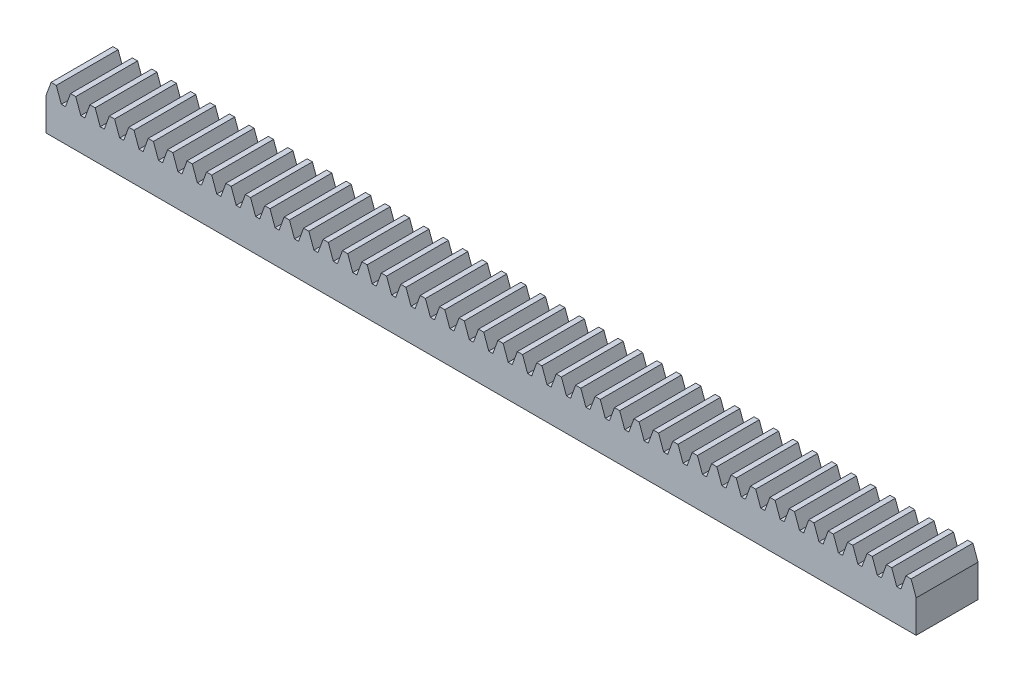
SolidWorks part; units mm, degrees
ref_plane "前视基准面" through (0, 0, 0) normal (0, 0, 1) x (1, 0, 0)
ref_plane "上视基准面" through (0, 0, 0) normal (0, 1, 0) x (1, 0, 0)
ref_plane "右视基准面" through (0, 0, 0) normal (1, 0, 0) x (0, 0, -1)
sketch "草图2" plane through (0, 0, 0) normal (0, 1, 0) x (1, 0, 0)
  line L1 (140.7108, -10) -> (-140.7108, -10)
  line L2 (140.7108, -10) -> (140.7108, 10)
  line L3 (140.7108, 10) -> (-140.7108, 10)
  line L4 (-140.7108, -10) -> (-140.7108, 10)
  line L5 (140.7108, -10) -> (-140.7108, 10) construction
  line L6 (140.7108, 10) -> (-140.7108, -10) construction
  point P0 (0, 0)
  dimension "D1" = 20
  dimension "D2" = 281.4216
extrude "凸台-拉伸1" add sketch "草图2" against normal blind 10.5
sketch "草图3" plane through (0, 0, 0) normal (0, 0, 1) x (1, 0, 0)
  line L0 (-140.7108, 0) -> (-139.0729, 4.5)
  line L1 (-139.0729, 4.5) -> (-137.3872, 4.5)
  line L2 (-137.3872, 4.5) -> (-135.7494, 0)
  line L3 (-140.7108, 0) -> (140.7108, 0) construction
  line L4 (-135.7494, 0) -> (-140.7108, 0)
  line L5 (-138.2301, 4.5) -> (-138.2301, 0) construction
  line L6 (-139.8009, 2.5) -> (-136.6593, 2.5) construction
  dimension "D1" = 2
  dimension "D2" = 2.5
  dimension "D3" = 40
  dimension "D4" = 3.1416
extrude "凸台-拉伸2" add sketch "草图3" along normal mid plane 20
pattern_linear "阵列(线性)1" count 45 spacing 6.2832 along (1, 0, 0) of "凸台-拉伸2"
sketch "分度线" plane through (0, 0, 0) normal (0, 0, 1) x (1, 0, 0)
  line L0 (-135.7494, 0) -> (-134.4276, 0) construction
  line L1 (-135.7494, 0) -> (-134.4276, 0)
  line L2 (-139.8009, 2.5) -> (108.3849, 2.5) construction
  line L3 (-139.0729, 4.5) -> (-140.7108, 0) construction
  line L4 (109.2949, 0) -> (107.657, 4.5) construction
  line L5 (-124.8209, 4.5) -> (-126.5066, 4.5) construction
  dimension "D1" = 1.3217
  dimension "D2" = 2
sketch "草图4" plane through (0, -10.5, 0) normal (0, -1, 0) x (1, 0, 0)
  line L1 (-140.7108, 10) -> (-79.2892, 10)
  line L2 (-140.7108, 10) -> (-140.7108, -10)
  line L3 (-140.7108, -10) -> (-79.2892, -10)
  line L4 (-79.2892, 10) -> (-79.2892, -10)
  line L5 (140.7108, 10) -> (140.7108, -10) construction
  line L6 (140.7108, -10) -> (-140.7108, -10) construction
  dimension "D1" = 220
equation "\"模数\"= 2"
equation "\"齿数\"= 45"
equation "\"压力角\"= 20"
equation "\"宽度\"= 20'齿条的宽度"
equation "\"高度\"= 15'齿条的总高度（从齿顶到最底面）"
equation "\"D1@草图3\"=\"模数\""
equation "\"D2@草图3\"=\"模数\"*1.25"
equation "\"D3@草图3\"=\"压力角\"*2"
equation "\"D4@草图3\"=\"模数\"*pi*0.5"
equation "\"D1@阵列(线性)1\"= \"齿数\""
equation "\"D3@阵列(线性)1\"=\"模数\"*pi"
equation "\"D1@草图2\"=\"宽度\""
equation "\"D1@凸台-拉伸2\"=\"宽度\""
equation "\"D2@草图2\" = \"模数\" * \"齿数\" * pi - \"D1@分度线\""
equation "\"D1@凸台-拉伸1\" = \"高度\" - \"模数\" * 2.25"
